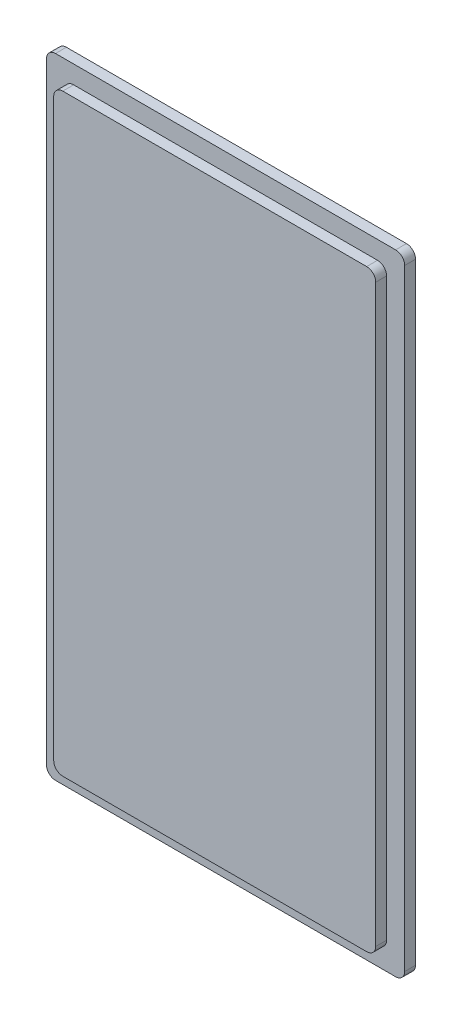
SolidWorks part; units mm, degrees
ref_plane "Front Plane" through (0, 0, 0) normal (0, 0, 1) x (1, 0, 0)
ref_plane "Top Plane" through (0, 0, 0) normal (0, 1, 0) x (1, 0, 0)
ref_plane "Right Plane" through (0, 0, 0) normal (1, 0, 0) x (0, 0, -1)
sketch "Sketch1" plane through (0, 0, 0) normal (0, 0, 1) x (1, 0, 0)
  line L0 (-60.3145, 37.0139) -> (-60.3145, -300.9861)
  line L1 (-55.3145, -305.9861) -> (132.6855, -305.9861)
  line L2 (137.6855, -300.9861) -> (137.6855, 37.0139)
  line L3 (132.6855, 42.0139) -> (-55.3145, 42.0139)
  arc A0 (-60.3145, -300.9861) -> (-55.3145, -305.9861) centre (-55.3145, -300.9861) ccw
  arc A1 (132.6855, -305.9861) -> (137.6855, -300.9861) centre (132.6855, -300.9861) ccw
  arc A2 (137.6855, 37.0139) -> (132.6855, 42.0139) centre (132.6855, 37.0139) ccw
  arc A3 (-60.3145, 37.0139) -> (-55.3145, 42.0139) centre (-55.3145, 37.0139) cw
  dimension "D1" = 5
extrude "Boss-Extrude1" add sketch "Sketch1" along normal blind 6
sketch "Sketch2" plane through (0, 0, 6) normal (0, 0, 1) x (1, 0, 0)
  line L0 (-50.3145, 27.0139) -> (-50.3145, -290.9861)
  line L1 (-60.3145, 37.0139) -> (-60.3145, -300.9861) construction
  line L2 (-55.3145, -305.9861) -> (132.6855, -305.9861) construction
  line L3 (132.6855, 42.0139) -> (-55.3145, 42.0139) construction
  line L4 (-45.3145, 32.0139) -> (122.6855, 32.0139)
  line L5 (137.6855, -300.9861) -> (137.6855, 37.0139) construction
  line L6 (127.6855, 27.0139) -> (127.6855, -290.9861)
  line L7 (-45.3145, -295.9861) -> (122.6855, -295.9861)
  arc A0 (-50.3145, 27.0139) -> (-45.3145, 32.0139) centre (-45.3145, 27.0139) cw
  arc A1 (122.6855, 32.0139) -> (127.6855, 27.0139) centre (122.6855, 27.0139) cw
  arc A2 (127.6855, -290.9861) -> (122.6855, -295.9861) centre (122.6855, -290.9861) cw
  arc A3 (-45.3145, -295.9861) -> (-50.3145, -290.9861) centre (-45.3145, -290.9861) cw
  point P14 (-50.3145, 32.0139)
  point P17 (127.6855, 32.0139)
  point P20 (127.6855, -295.9861)
  point P23 (-50.3145, -295.9861)
  dimension "D6" = 5
  dimension "D1" = 10
  dimension "D2" = 10
  dimension "D3" = 10
  dimension "D4" = 10
  dimension "D5" = 10
extrude "Boss-Extrude2" add sketch "Sketch2" along normal blind 6
